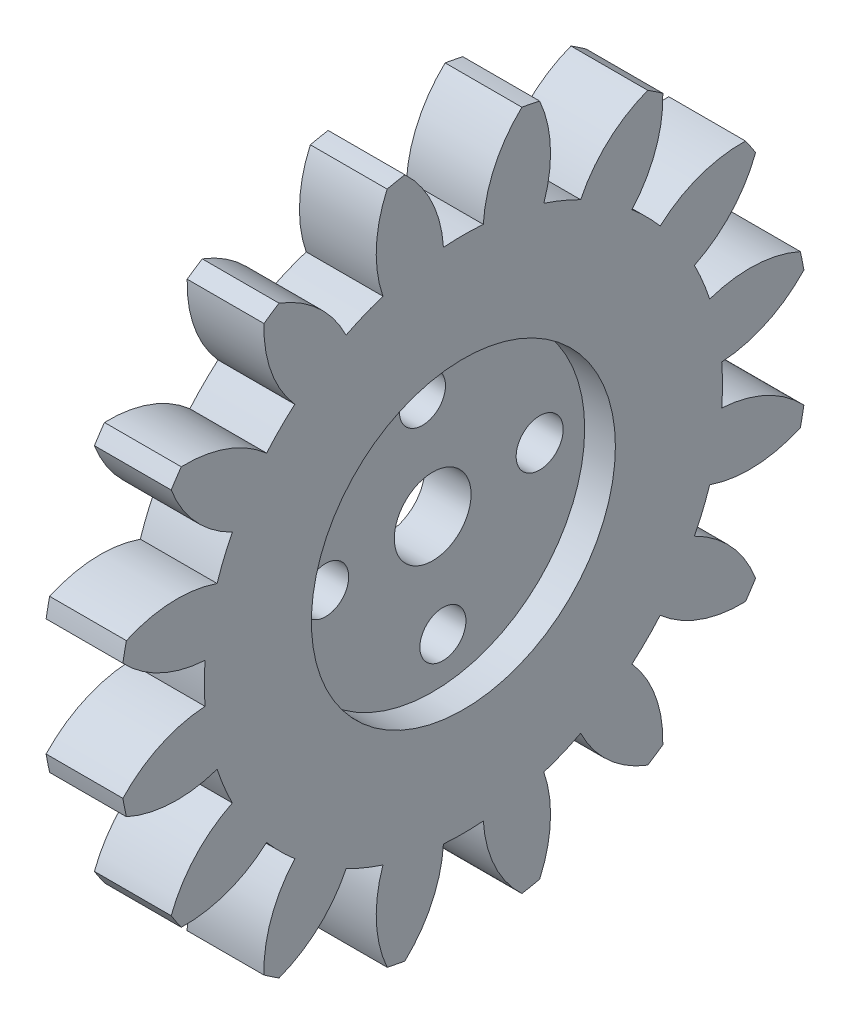
SolidWorks part; units mm, degrees
ref_plane "Plane1" through (0, 0, 0) normal (0, 0, 1) x (1, 0, 0)
ref_plane "Plane2" through (0, 0, 0) normal (0, 1, 0) x (1, 0, 0)
ref_plane "Plane3" through (0, 0, 0) normal (1, 0, 0) x (0, 0, -1)
other "Configuration Table"
sketch "HoldingSke" plane through (0, 0, 0) normal (0, 1, 0) x (1, 0, 0)
  line L0 (0, 0) -> (0.3845, -0.1103)
  line L1 (-15, 0) -> (100, 0) construction
  line L2 (0, 0) -> (-2.1039, 2.3779)
  line L3 (0, 0) -> (-11.863, 4.5341)
  line L4 (0, 0) -> (8.3015, 2.3804)
  line L5 (0, 0) -> (-46.8476, -17.4728)
  line L6 (0, 0) -> (-4.1448, -2.7965)
  line L7 (-2.1039, 2.3779) -> (8.6586, 51.2059)
  line L8 (-76.2, 54.61) -> (-75.3, 54.61)
  line L9 (-71.009, 38.7566) -> (-53.1078, 45.2721)
  line L10 (-76.2, 71.12) -> (104.1128, 71.12)
  line L11 (0, 0) -> (-5, 0)
  line L12 (-76.2, 101.6) -> (-76.113, 101.6)
  line L13 (24.9733, 27.94) -> (52.9518, 28.4284)
  line L14 (24.9733, 27.94) -> (24.9743, 27.94)
  line L15 (24.9733, 27.94) -> (100.4006, 29.5858)
  line L16 (-63.627, -2.5) -> (-12.827, -2.5)
  circle A0 centre (0, 0) radius 2.5
  circle A1 centre (0, 0) radius 16.874
  circle A2 centre (0, 0) radius 37.5
  circle A3 centre (0, 0) radius 2.5
  dimension "MHD" = 33.748
  dimension "Hub_dia" = 75
  dimension "Bore" = 5
  dimension "MBD" = 5
  dimension "Num_teeth" = 16
  dimension "Pitch" = 0.4
  dimension "Overall_len" = 50
  dimension "Show_teeth" = 16
  dimension "Thickness" = 5
  dimension "OAL" = 50.0001
  dimension "T_dim" = 0.9
  dimension "Ap" = 20
  dimension "H" = 19.05
  dimension "Pitch_radius" = 180.3128
  dimension "Width" = 5
  dimension "Backlash" = 0.087
  dimension "Addendum_fac" = 1
  dimension "Dedendum_fac" = 1.25
  dimension "Clearance_fac" = 0.25
  dimension "Dedendum_add" = 0.001
  dimension "Module" = 2.5
sketch "BasProSke" plane through (0, 0, 0) normal (0, 1, 0) x (1, 0, 0)
  line L0 (-10, 0) -> (60, 0) construction
  line L1 (0, 0) -> (0, 22.5)
  line L2 (0, 0) -> (5, 0)
  line L3 (5, 0) -> (5, 22.5)
  line L4 (5, 22.5) -> (0, 22.5)
  dimension "Thickness" = 5
  dimension "Diameter" = 45
revolve "Base-Revolve" add sketch "BasProSke" angle 360 about L0
sketch "TooCutSke" plane through (0, 0, 0) normal (1, 0, 0) x (0, 0, -1)
  line L1 (0, 0) -> (0, 107) construction
  line L2 (0, 0) -> (-2.1125, 19.8881) construction
  line L3 (0, 0) -> (-7.7717, 39.0708) construction
  line L4 (-2.1125, 19.8881) -> (-3.8858, 19.5354) construction
  arc A0 (1.2977, 16.824) -> (-1.2977, 16.824) centre (0, 0) ccw
  arc A1 (3.8326, 22.197) -> (-3.8326, 22.197) centre (0, 0) ccw
  circle A2 centre (0, 0) radius 20 construction
  circle A3 centre (0, 0) radius 18.7939 construction
  arc A4 (-1.2977, 16.824) -> (-3.8326, 22.197) centre (-9.2832, 16.3411) ccw
  arc A5 (3.8326, 22.197) -> (1.2977, 16.824) centre (9.2832, 16.3411) ccw
  dimension "Root_dia" = 33.748
  dimension "Overcut_dia" = 45.0508
  dimension "Pitch_dia" = 40
  dimension "Base_dia" = 37.5877
  dimension "Flank_rad" = 8
  dimension "Half_ang" = 11.25
  dimension "Half_CT" = 1.8081
extrude "ToothCut" cut sketch "TooCutSke" along normal through all
fillet "Breaks" [suppressed] radius 0.05
fillet "RootFillets" [suppressed] radius 0.626
pattern_circular "TeethCuts" count 16 every 22.5 about axis through (-10, 0, 0) along (1, 0, 0) of "ToothCut", "RootFillets", "Breaks"
sketch "HubNeaOneSke" plane through (0, 0, 0) normal (-1, 0, 0) x (0, 0, 1)
  circle A0 centre (0, 0) radius 16.874
  dimension "Diameter" = 33.748
extrude "HubNearOne" [suppressed] add sketch "HubNeaOneSke" along normal blind 45.0001
sketch "HubNeaBotSke" plane through (0, 0, 0) normal (-1, 0, 0) x (0, 0, 1)
  circle A0 centre (0, 0) radius 16.874
  dimension "Diameter" = 33.748
extrude "HubNearBoth" [suppressed] add sketch "HubNeaBotSke" along normal blind 22.5
ref_plane "FarPln" through (5, 0, 0) normal (1, 0, 0) x (0, 0, -1)
sketch "HubFarSke" plane through (5, 0, 0) normal (1, 0, 0) x (0, 0, -1)
  circle A0 centre (0, 0) radius 16.874
  dimension "Diameter" = 33.748
extrude "HubFar" [suppressed] add sketch "HubFarSke" along normal blind 22.5
sketch "BorSke" plane through (0, 0, 0) normal (1, 0, 0) x (0, 0, -1)
  circle A0 centre (0, 0) radius 2.5
  dimension "Diameter" = 5
extrude "Bore" cut sketch "BorSke" along normal mid plane 100.0001
sketch "KeySke" plane through (0, 0, 0) normal (1, 0, 0) x (0, 0, -1)
  line L0 (-1, 0) -> (-1, 3.4)
  line L1 (-1, 3.4) -> (1, 3.4)
  line L2 (1, 3.4) -> (1, 0)
  line L3 (0, 0) -> (0, 34) construction
  line L4 (-1, 0) -> (1, 0)
  dimension "Offset" = 3.4
  dimension "Width" = 2
extrude "Keyway" [suppressed] cut sketch "KeySke" along normal mid plane 100.0001
pattern_circular "Keyway2" [suppressed] count 2 every 90 about axis through (-10, 0, 0) along (1, 0, 0)
sketch "Esquisse1" plane through (5, 0, 0) normal (1, 0, 0) x (0, 0, -1)
  circle A0 centre (0, 0) radius 9.9
extrude "Enlèv. mat.-Extru.1" cut sketch "Esquisse1" against normal blind 2
sketch "Esquisse2" plane through (3, 0, 0) normal (1, 0, 0) x (0, 0, -1)
  circle A1 centre (-0.6659, 6.9683) radius 1.5
  circle A2 centre (6.9683, 0.6659) radius 1.5313
  circle A3 centre (0.6659, -6.9683) radius 1.5
  circle A4 centre (-6.9683, -0.6659) radius 1.5
extrude "Enlèv. mat.-Extru.2" cut sketch "Esquisse2" against normal through all
equation "' \"Module@HoldingSke\" = 6.35"
equation "' \"Num_teeth@HoldingSke\" = 12"
equation "' \"Ap@HoldingSke\" =  20"
equation "' \"Ap@HoldingSke\" = 20"
equation "' \"Width@HoldingSke\" = 0.5 * 25.4"
equation "' \"Hub_dia@HoldingSke\"= 1 * 25.4"
equation "' \"Hub_dia@HoldingSke\" = 1 * 25.4"
equation "' \"Overall_len@HoldingSke\" = 1.0 * 25.4"
equation "' \"Bore@HoldingSke\" = 0.75 * 25.4"
equation "' \"T_dim@HoldingSke\" = 0.1 * 25.4"
equation "' \"Width@KeySke\" = 0.25 * 25.4"
equation "' \"Show_teeth@HoldingSke\" = 13"
equation "' \"Backlash@HoldingSke\" = 0.009 * 25.4"
equation "' \"Addendum_fac@HoldingSke\" = 1.0"
equation "' \"Dedendum_fac@HoldingSke\" = 1.25"
equation "' \"Dedendum_add@HoldingSke\" = 0.00005 * 25.4"
equation "' \"Clearance_fac@HoldingSke\" = 0.25"
equation "\"Pitch@HoldingSke\" = 1 / \"Module@HoldingSke\""
equation "\"Overcut_dia@TooCutSke\" = (\"Num_teeth@HoldingSke\" + 2 * \"Addendum_fac@HoldingSke\") / \"Pitch@HoldingSke\" + 0.002 * 25.4"
equation "\"Pitch_dia@TooCutSke\" = \"Num_teeth@HoldingSke\" / \"Pitch@HoldingSke\""
equation "\"Base_dia@TooCutSke\" = \"Num_teeth@HoldingSke\" / \"Pitch@HoldingSke\" * cos((\"Ap@HoldingSke\"  * 3.14159265 / 180))"
equation "\"Root_dia@TooCutSke\" = (\"Num_teeth@HoldingSke\" + 2) / \"Pitch@HoldingSke\" - 2 * (\"Addendum_fac@HoldingSke\" + \"Dedendum_fac@HoldingSke\") / \"Pitch@HoldingSke\" - \"Dedendum_add@HoldingSke\" * 2"
equation "\"Half_ang@TooCutSke\" = 180 / \"Num_teeth@HoldingSke\""
equation "\"Half_CT@TooCutSke\" = \"Num_teeth@HoldingSke\" / \"Pitch@HoldingSke\" * sin((3.14159265 / 2 / \"Num_teeth@HoldingSke\")) / 2 - 7 * \"Backlash@HoldingSke\" / 4"
equation "\"Flank_rad@TooCutSke\" = \"Num_teeth@HoldingSke\" / \"Pitch@HoldingSke\" / 5"
equation "\"Radius@RootFillets\" = \"Clearance_fac@HoldingSke\" / \"Pitch@HoldingSke\" + \"Dedendum_add@HoldingSke\""
equation "\"Break_rad@Breaks\" = 0.02 / \"Pitch@HoldingSke\""
equation "\"Thickness@HoldingSke\" = \"Width@HoldingSke\""
equation "\"OAL@HoldingSke\" = \"Thickness@HoldingSke\""
equation "\"MHD@HoldingSke\" = (\"Num_teeth@HoldingSke\" + 2) / \"Pitch@HoldingSke\" - 2 * (\"Addendum_fac@HoldingSke\" + \"Dedendum_fac@HoldingSke\")  / \"Pitch@HoldingSke\" - \"Dedendum_add@HoldingSke\" * 2"
equation "\"MBD@HoldingSke\" = (\"Num_teeth@HoldingSke\" + 2) / \"Pitch@HoldingSke\" - 2 * (\"Addendum_fac@HoldingSke\" + \"Dedendum_fac@HoldingSke\")  / \"Pitch@HoldingSke\" - \"Dedendum_add@HoldingSke\" * 2 - 0.002 * 25.4"
equation "\"MHD@HoldingSke\" = ((sgn( \"MHD@HoldingSke\" - \"Hub_dia@HoldingSke\" )-1)*( \"MHD@HoldingSke\" - \"Hub_dia@HoldingSke\" ))/-2+ \"Hub_dia@HoldingSke\""
equation "\"MBD@HoldingSke\" = ((sgn( \"MBD@HoldingSke\" - \"Bore@HoldingSke\" )-1)*( \"MBD@HoldingSke\" - \"Bore@HoldingSke\" ))/-2+ \"Bore@HoldingSke\""
equation "\"OAL@HoldingSke\" = ((sgn( \"OAL@HoldingSke\" - \"Overall_len@HoldingSke\" )+1)*( \"OAL@HoldingSke\" - \"Overall_len@HoldingSke\" ))/2 + \"Overall_len@HoldingSke\" + 0.000002 * 25.4"
equation "\"Num_teeth@TeethCuts\" = int( \"Show_teeth@HoldingSke\" ) + 1"
equation "\"Num_teeth@TeethCuts\" = ((sgn( \"Num_teeth@TeethCuts\" - \"Num_teeth@HoldingSke\" )-1)*( \"Num_teeth@TeethCuts\" - \"Num_teeth@HoldingSke\" ))/-2+ \"Num_teeth@HoldingSke\""
equation "\"Num_teeth@TeethCuts\" = ((sgn( \"Num_teeth@TeethCuts\" - 2.0)+1)*( \"Num_teeth@TeethCuts\" - 2.0))/2 +2.0"
equation "\"Angle@TeethCuts\" = 360.0 / \"Num_teeth@HoldingSke\""
equation "\"Diameter@BasProSke\" = (\"Num_teeth@HoldingSke\" + 2 * \"Addendum_fac@HoldingSke\") / \"Pitch@HoldingSke\""
equation "\"Thickness@BasProSke\"  = \"Thickness@HoldingSke\""
equation "' \"Fillet_rad@BasProSke\" =  \"Thickness@HoldingSke\" * 0.05"
equation "' \"Fillet_rad@BasProSke\" = \"Thickness@HoldingSke\" * 0.05"
equation "\"MHD@HoldingSke\" = ((sgn( \"MHD@HoldingSke\" - \"Root_dia@TooCutSke\" )-1)*( \"MHD@HoldingSke\" - \"Root_dia@TooCutSke\" ))/-2+ \"Root_dia@TooCutSke\""
equation "\"Diameter@HubNeaOneSke\" = \"MHD@HoldingSke\""
equation "\"Length@HubNearOne\" = \"OAL@HoldingSke\" - \"Thickness@BasProSke\""
equation "\"Diameter@HubNeaBotSke\" = \"MHD@HoldingSke\""
equation "\"Length@HubNearBoth\" = ( \"OAL@HoldingSke\" - \"Thickness@BasProSke\" ) / 2.0"
equation "\"Thickness@FarPln\" = \"Thickness@BasProSke\""
equation "\"Diameter@HubFarSke\" = \"MHD@HoldingSke\""
equation "\"Length@HubFar\" = ( \"OAL@HoldingSke\" - \"Thickness@BasProSke\" ) / 2.0"
equation "\"Diameter@BorSke\" = \"MBD@HoldingSke\""
equation "\"D1@Bore\" = \"OAL@HoldingSke\" * 2.0"
equation "\"D1@Keyway\" = \"OAL@HoldingSke\" * 2.0"
equation "\"Offset@KeySke\" = \"T_dim@HoldingSke\" + \"MBD@HoldingSke\" / 2.0"
